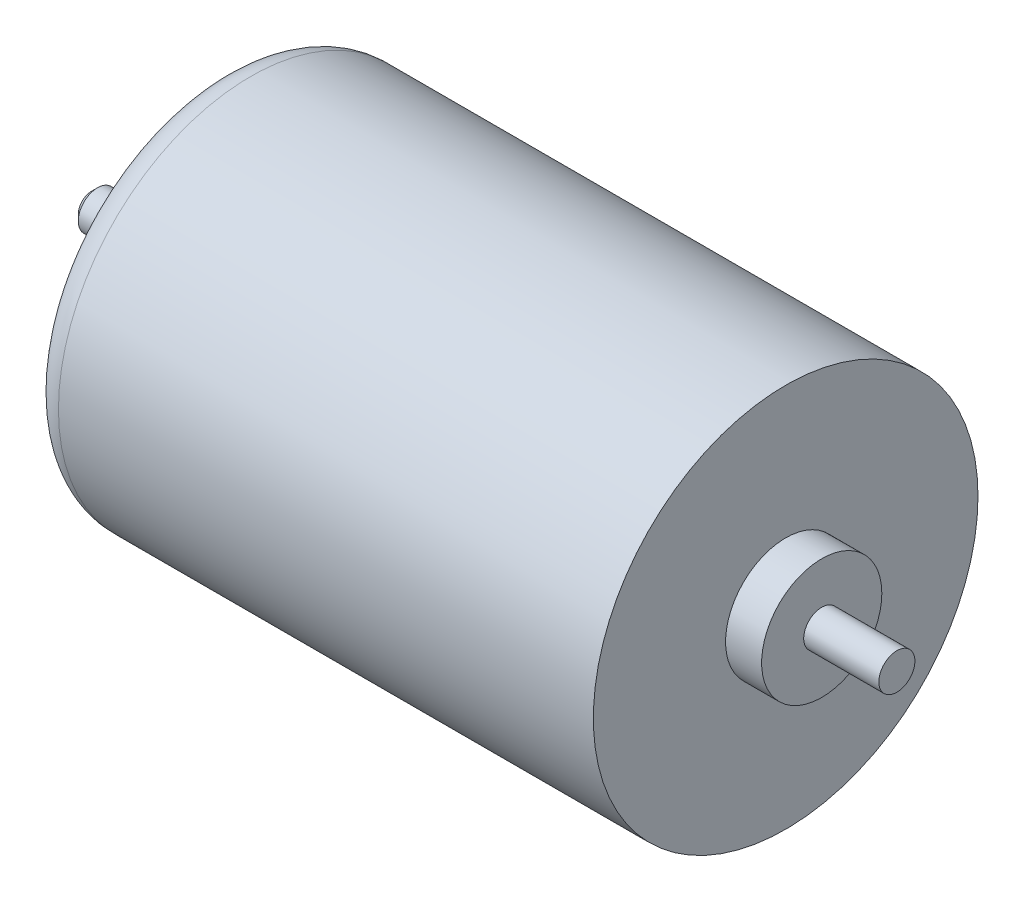
SolidWorks part; units mm, degrees
ref_plane "Alzado" through (0, 0, 0) normal (1, 0, 0) x (0, 1, 0)
ref_plane "Planta" through (0, 0, 0) normal (0, 0, 1) x (0, 1, 0)
ref_plane "Vista lateral" through (0, 0, 0) normal (0, 1, 0) x (-1, 0, 0)
sketch "Croquis1" plane through (0, 0, 0) normal (0, 0, 1) x (0, 1, 0)
  line L0 (0, 0) -> (0, 67) construction
  line L1 (0, 0) -> (1.5, 0)
  line L2 (1.5, 0) -> (1.5, 6.25)
  line L3 (1.5, 6.25) -> (5, 6.25)
  line L4 (5, 6.25) -> (5, 9.25)
  line L5 (5, 9.25) -> (16, 9.25)
  line L6 (16, 9.25) -> (16, 56.25)
  line L7 (0, 67) -> (1.6, 67)
  line L8 (1.6, 67) -> (1.6, 59.85)
  line L9 (1.6, 59.85) -> (5, 59.85)
  line L10 (5, 59.85) -> (5, 56.25)
  line L11 (5, 56.25) -> (16, 56.25)
  line L12 (0, 0) -> (0, 67)
  point P3 (0, 0)
  dimension "D1" = 67
  dimension "D2" = 1.5
  dimension "D3" = 6.25
  dimension "D4" = 5
  dimension "D5" = 3
  dimension "D6" = 16
  dimension "D7" = 47
  dimension "D8" = 5
  dimension "D9" = 3.6
  dimension "D10" = 1.6
revolve "Revolución1" add sketch "Croquis1" angle 360 about L0
fillet "Redondeo1" radius 2.5 1 edges at (-56.25, 0, -16)
sketch "Croquis2" plane through (-56.25, 0, 0) normal (-1, 0, 0) x (0, -1, 0)
  line L0 (0, 0) -> (0, -12.561) construction
  point P0 (-10.3, 0)
  point P1 (10.3, 0)
  dimension "D1" = 20.6
hole_wizard "Taladro roscado M3x0.51" positions "Croquis2" profile "Croquis4" tap size "M3x0.5" standard "Ansi Metric"
sketch "Croquis4" plane through (-56.25, 10.3, 0) normal (0, 1, 0) x (0, 0, 1)
  line L0 (0, 0) -> (0, 9.2511)
  line L1 (0, 9.2511) -> (1.25, 8.5)
  line L2 (1.25, 8.5) -> (1.25, 0)
  line L5 (1.25, 0) -> (0, 0)
  line L10 (0, 9.2511) -> (-1.25, 8.5) construction
  line L11 (0, -6.35) -> (0, 107.95) construction
  dimension "Diámetro de perforador para roscar" = 2.5
  dimension "Profundidad de perforador para roscar" = 8.5
  dimension "Ángulo de perforador" = 118
cosmetic thread "Rosca de taladro3" parameters "D1"=6, "D2"=3
cosmetic thread "Rosca de taladro4" parameters "D1"=6, "D2"=3
chamfer "Chaflán1" distance 0.5 angle 45 1 edges at (-67, 0, -1.6)
